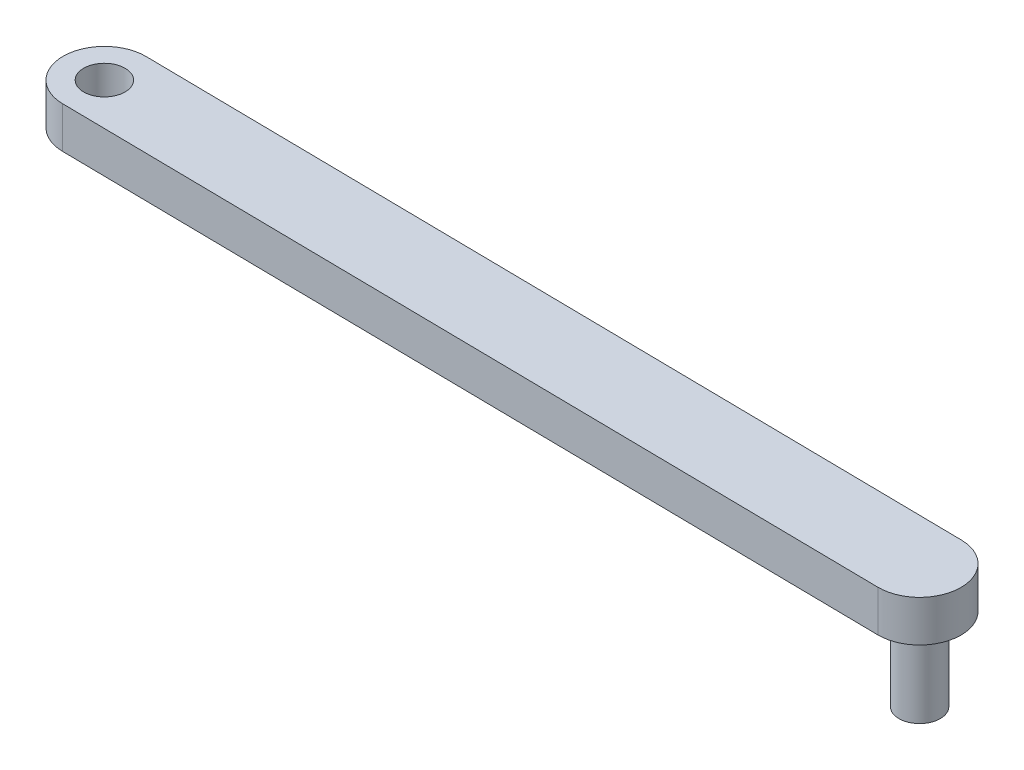
SolidWorks part; units mm, degrees
ref_plane "Front Plane" through (0, 0, 0) normal (0, 0, 1) x (1, 0, 0)
ref_plane "Top Plane" through (0, 0, 0) normal (0, 1, 0) x (1, 0, 0)
ref_plane "Right Plane" through (0, 0, 0) normal (1, 0, 0) x (0, 0, -1)
sketch "Sketch1" plane through (0, 0, 0) normal (0, 1, 0) x (1, 0, 0)
  line L0 (-14.5716, 1.7071) -> (85.4284, 0.3636) construction
  line L1 (-14.5044, 6.7067) -> (85.4956, 5.3631)
  line L2 (-14.6388, -3.2924) -> (85.3612, -4.636)
  arc A0 (-14.5044, 6.7067) -> (-14.6388, -3.2924) centre (-14.5716, 1.7071) ccw
  arc A1 (85.3612, -4.636) -> (85.4956, 5.3631) centre (85.4284, 0.3636) ccw
  circle A2 centre (-14.5716, 1.7071) radius 2.5
  point P2 (35.4284, 1.0354)
  dimension "D2" = 5
  dimension "D1" = 100
  dimension "D3" = 10
  dimension "D4" = 0
extrude "Boss-Extrude1" add sketch "Sketch1" along normal blind 5
sketch "Sketch2" plane through (0, 5, 0) normal (0, 1, 0) x (1, 0, 0)
  line L0 (-14.6388, -3.2924) -> (85.3612, -4.636) construction
  circle A0 centre (85.4284, 0.3636) radius 2.5
  circle A1 centre (-14.5716, 1.7071) radius 2.5 construction
  dimension "D2" = 5
  dimension "D1" = 100
  dimension "D3" = 5
extrude "Boss-Extrude2" add sketch "Sketch2" against normal blind 15
